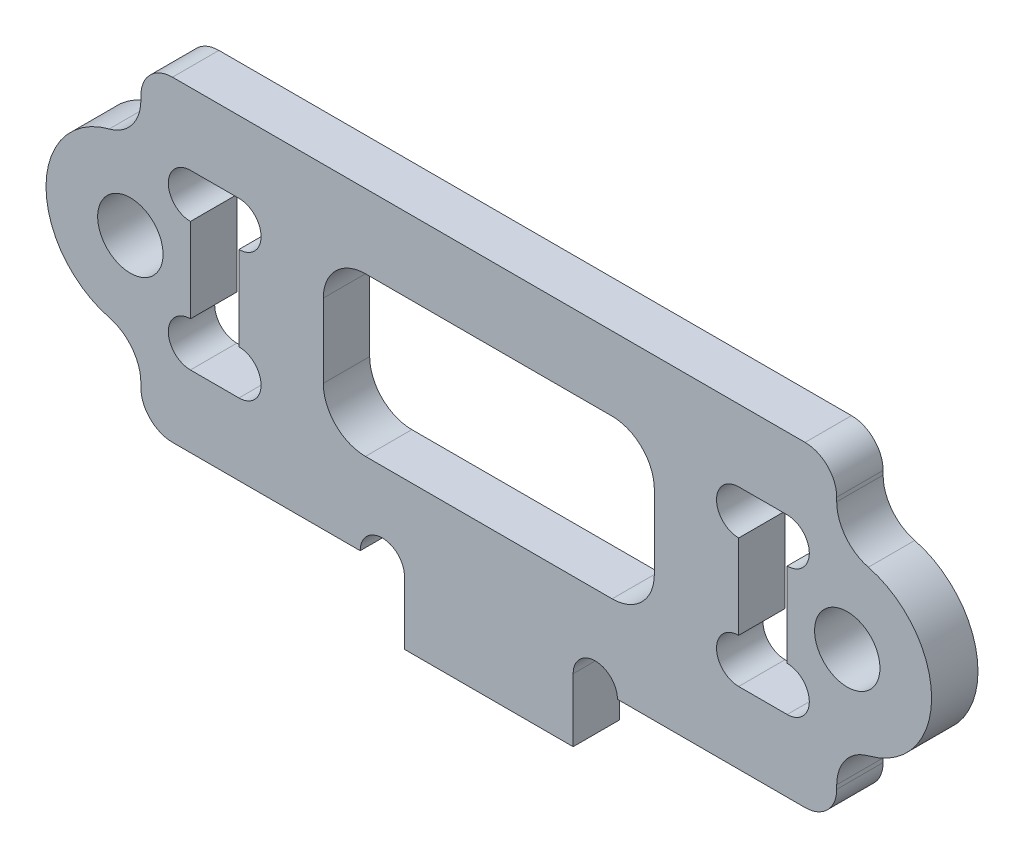
SolidWorks part; units mm, degrees
material "Thornel Mat VMA"
ref_plane "前视基准面" through (0, 0, 0) normal (0, 0, 1) x (1, 0, 0)
ref_plane "上视基准面" through (0, 0, 0) normal (0, 1, 0) x (1, 0, 0)
ref_plane "右视基准面" through (0, 0, 0) normal (1, 0, 0) x (0, 0, -1)
sketch "草图1" plane through (0, 0, 0) normal (0, 0, 1) x (1, 0, 0)
  line L0 (0, 0) -> (0, -10.5) construction
  line L1 (-16.5, -3.9686) -> (-16.5, -7.5)
  line L2 (-16.5, -7.5) -> (-4, -7.5)
  line L3 (16.5, -3.9686) -> (16.5, -7.5)
  line L4 (0, 0) -> (5.1275, 0) construction
  line L5 (16.5, 3.9686) -> (16.5, 7.5)
  line L6 (-16.5, 7.5) -> (16.5, 7.5)
  line L7 (-16.5, 3.9686) -> (-16.5, 7.5)
  line L8 (11.85, -4.1) -> (14.15, 4.1) construction
  line L9 (-11.85, 4.1) -> (-14.15, 4.1)
  line L10 (-11.85, 4.1) -> (-11.85, -4.1)
  line L11 (-11.85, -4.1) -> (-14.15, -4.1)
  line L12 (-14.15, 4.1) -> (-14.15, -4.1)
  line L13 (-11.85, 4.1) -> (-14.15, -4.1) construction
  line L14 (-11.85, -4.1) -> (-14.15, 4.1) construction
  line L15 (11.85, 4.1) -> (14.15, -4.1) construction
  line L16 (14.15, 4.1) -> (14.15, -4.1)
  line L17 (11.85, -4.1) -> (14.15, -4.1)
  line L18 (11.85, 4.1) -> (11.85, -4.1)
  line L19 (11.85, 4.1) -> (14.15, 4.1)
  line L20 (-4, -7.5) -> (-4, -10.5)
  line L21 (-4, -10.5) -> (4, -10.5)
  line L22 (4, -10.5) -> (4, -7.5)
  line L23 (4, -7.5) -> (16.5, -7.5)
  line L25 (7.85, 4) -> (-7.85, 4)
  line L26 (7.85, 4) -> (7.85, -3.5)
  line L27 (7.85, -3.5) -> (-7.85, -3.5)
  line L28 (-7.85, 4) -> (-7.85, -3.5)
  line L29 (7.85, 4) -> (-7.85, -3.5) construction
  line L30 (7.85, -3.5) -> (-7.85, 4) construction
  circle A0 centre (-17, 0) radius 1.55
  circle A1 centre (17, 0) radius 1.55
  arc A2 (-16.5, 3.9686) -> (-16.5, -3.9686) centre (-17, 0) ccw
  arc A3 (16.5, 3.9686) -> (16.5, -3.9686) centre (17, 0) cw
  circle A4 centre (-11.85, -3.05) radius 1.05
  circle A5 centre (-14.15, -3.05) radius 1.05
  circle A6 centre (-11.85, 3.05) radius 1.05
  circle A7 centre (-14.15, 3.05) radius 1.05
  circle A8 centre (14.15, 3.05) radius 1.05
  circle A9 centre (11.85, 3.05) radius 1.05
  circle A10 centre (14.15, -3.05) radius 1.05
  circle A11 centre (11.85, -3.05) radius 1.05
  circle A12 centre (5.05, -7.5) radius 1.05
  circle A13 centre (-5.05, -7.5) radius 1.05
  point P7 (-13, 0)
  point P41 (13, 0)
  point P50 (0, 0.25)
  dimension "D1" = 3.1
  dimension "D3" = 8
  dimension "D6" = 2.1
  dimension "D2" = 34
  dimension "D4" = 33
  dimension "D5" = 7.5
  dimension "D7" = 2.3
  dimension "D8" = 8.2
  dimension "D9" = 26
  dimension "D10" = 3
  dimension "D11" = 8
  dimension "D12" = 3.5
  dimension "D13" = 4
  dimension "D14" = 4
extrude "凸台-拉伸1" add sketch "草图1" along normal blind 2.2 contours A3 L5 L6 L7 A2 L1 L2 L3 A7 L9 A6 L10 A4 L11 A5 L12 A0 A1 L17 A11 L18 A9 L19 A8 L16 A10
fillet "圆角1" radius 2 4 edges at (16.5, -3.9686, 1.1) (16.5, 3.9686, 1.1) (-16.5, 3.9686, 1.1) (-16.5, -3.9686, 1.1)
fillet "圆角2" radius 1.5 4 edges at (-16.5, 7.5, 1.1) (16.5, 7.5, 1.1) (-16.5, -7.5, 1.1) (16.5, -7.5, 1.1)
fillet "圆角3" radius 2 4 edges at (7.85, -3.5, 1.1) (7.85, 4, 1.1) (-7.85, 4, 1.1) (-7.85, -3.5, 1.1)
